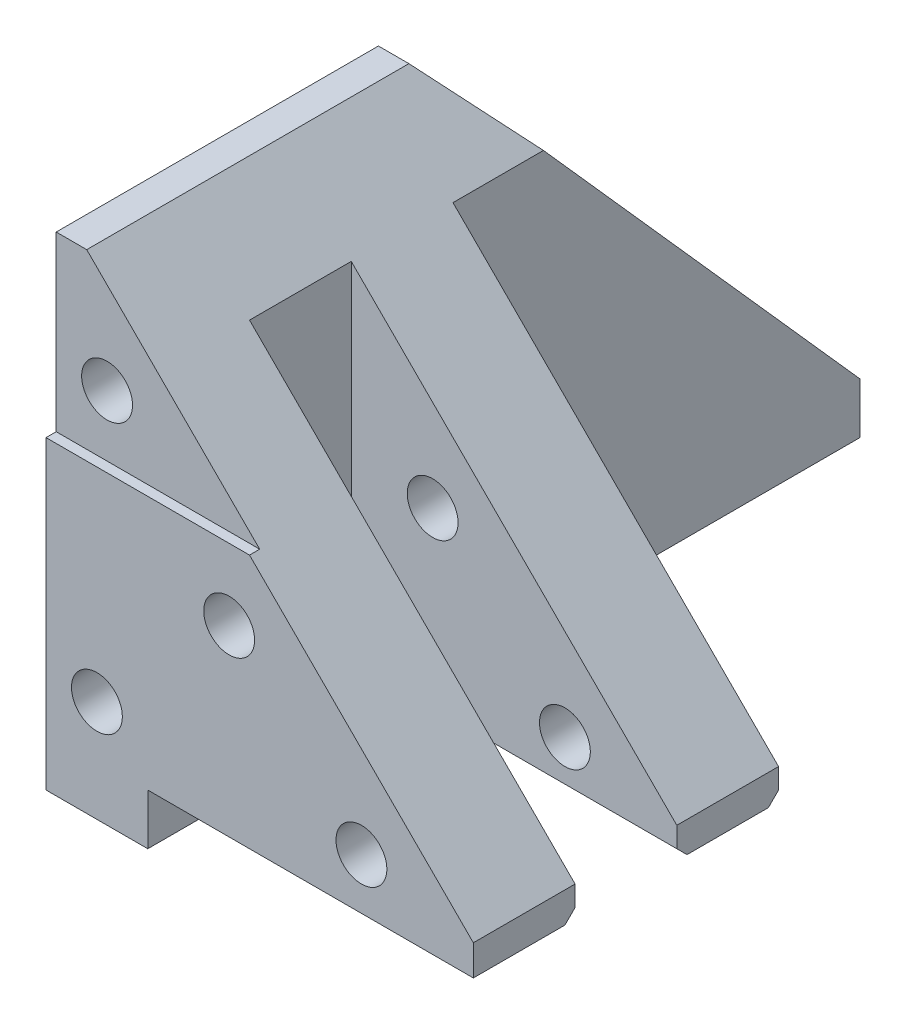
SolidWorks part; units mm, degrees
ref_plane "前视基准面" through (0, 0, 0) normal (0, 0, 1) x (1, 0, 0)
ref_plane "上视基准面" through (0, 0, 0) normal (0, 1, 0) x (1, 0, 0)
ref_plane "右视基准面" through (0, 0, 0) normal (1, 0, 0) x (0, 0, -1)
sketch "草图1" plane through (0, 0, 0) normal (0, 0, 1) x (1, 0, 0)
  line L0 (0, 0) -> (50, 0)
  line L1 (50, 0) -> (0, 50)
  line L2 (0, 50) -> (0, 0)
  dimension "D1" = 50
extrude "拉伸1" add sketch "草图1" along normal blind 70
sketch "草图3" plane through (0, 0, 70) normal (0, 0, 1) x (1, 0, 0)
  line L0 (50, 0) -> (42, 0)
  line L1 (0, 0) -> (50, 0) construction
  line L2 (42, 0) -> (42, 8)
  line L3 (50, 0) -> (0, 50) construction
  line L4 (42, 8) -> (50, 0)
  line L5 (0, 50) -> (0, 0) construction
  dimension "D1" = 42
extrude "切除-拉伸1" cut sketch "草图3" against normal through all
sketch "草图4" plane through (0, 0, 70) normal (0, 0, 1) x (1, 0, 0)
  line L0 (0, 0) -> (42, 0) construction
  line L1 (10, 0) -> (55.8197, 0)
  line L2 (10, 0) -> (10, 5)
  line L3 (10, 5) -> (55.8197, 5)
  line L4 (55.8197, 0) -> (55.8197, 5)
  line L5 (0, 50) -> (0, 0) construction
  dimension "D1" = 10
  dimension "D2" = 5
extrude "切除-拉伸2" cut sketch "草图4" against normal through all
sketch "草图5" plane through (0, 5, 0) normal (0, -1, 0) x (1, 0, 0)
  line L0 (42, 70) -> (42, 0) construction
  line L1 (42, 60) -> (10, 60)
  line L2 (42, 60) -> (42, 50)
  line L3 (42, 50) -> (10, 50)
  line L4 (10, 60) -> (10, 50)
  line L5 (10, 0) -> (10, 70) construction
  line L6 (10, 0) -> (10, 70) construction
  line L7 (42, 40) -> (10, 40)
  line L8 (42, 40) -> (42, 0)
  line L9 (42, 0) -> (10, 0)
  line L10 (10, 40) -> (10, 0)
  line L11 (42, 70) -> (10, 70) construction
  dimension "D1" = 10
  dimension "D2" = 10
  dimension "D3" = 10
extrude "切除-拉伸3" cut sketch "草图5" against normal through all
sketch "草图6" plane through (0, 0, 70) normal (0, 0, 1) x (1, 0, 0)
  line L0 (0, 50) -> (0, 30)
  line L1 (0, 50) -> (0, 0) construction
  line L2 (0, 30) -> (20, 30)
  line L3 (42, 8) -> (0, 50) construction
  line L4 (20, 30) -> (0, 50)
  line L5 (0, 0) -> (10, 0) construction
  dimension "D1" = 30
extrude "切除-拉伸4" cut sketch "草图6" against normal blind 1
sketch "草图7" plane through (0, 5, 0) normal (0, -1, 0) x (1, 0, 0)
  line L0 (42, 70) -> (10, 70) construction
  line L1 (0, 70) -> (0, 0) construction
  circle A0 centre (16, 65) radius 3.75
  dimension "D1" = 7.5
  dimension "D2" = 5
  dimension "D3" = 16
extrude "切除-拉伸5" cut sketch "草图7" against normal blind 10
sketch "草图8" plane through (0, 0, 70) normal (0, 0, 1) x (1, 0, 0)
  line L0 (5, 36) -> (31, 10) construction
  line L1 (31, 10) -> (5, 10) construction
  line L2 (5, 10) -> (5, 36) construction
  line L3 (42, 8) -> (20, 30) construction
  line L4 (0, 0) -> (10, 0) construction
  line L5 (0, 30) -> (0, 0) construction
  circle A0 centre (5, 36) radius 2.5
  circle A1 centre (5, 10) radius 2.5
  circle A2 centre (31, 10) radius 2.5
  circle A3 centre (18, 23) radius 2.5
  dimension "D1" = 5
  dimension "D2" = 10
  dimension "D3" = 5
  dimension "D4" = 26
extrude "切除-拉伸6" cut sketch "草图8" against normal up to surface (30 mm away) up to face at (26, 14.5, 40)
sketch "草图9" plane through (10, 0, 0) normal (1, 0, 0) x (0, 0, -1)
  line L0 (0, 50) -> (-40, 50)
  line L1 (-69, 50) -> (0, 50) construction
  line L2 (-40, 50) -> (0, 5)
  line L5 (-40, 40) -> (-40, 54.9233) construction
  line L6 (0, 40) -> (0, 0) construction
  line L7 (0, 0) -> (-70, 0) construction
  dimension "D1" = 5
extrude "切除-拉伸7" cut sketch "草图9" against normal through all and the other way through all
sketch "草图10" plane through (0, 0, 69) normal (0, 0, 1) x (1, 0, 0)
  line L0 (0, 50) -> (0, 47)
  line L1 (0, 50) -> (0, 30) construction
  line L2 (0, 47) -> (3, 47)
  line L3 (20, 30) -> (0, 50) construction
  line L4 (3, 47) -> (0, 50)
  dimension "D1" = 3
extrude "切除-拉伸8" cut sketch "草图10" against normal through all
chamfer "倒角1" distance 1 angle 45 3 edges at (26, 5, 40) (26, 5, 50) (26, 5, 60)
